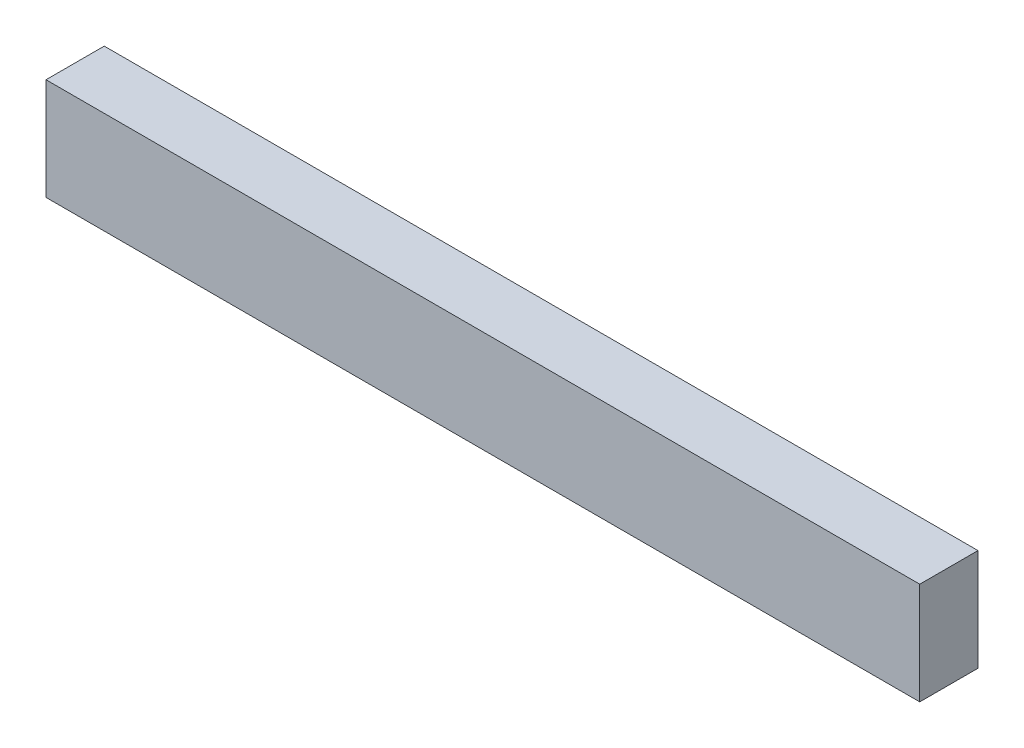
SolidWorks part; units mm, degrees
ref_plane "Front Plane" through (0, 0, 0) normal (0, 0, 1) x (1, 0, 0)
ref_plane "Top Plane" through (0, 0, 0) normal (0, 1, 0) x (1, 0, 0)
ref_plane "Right Plane" through (0, 0, 0) normal (1, 0, 0) x (0, 0, -1)
sketch "Sketch1" plane through (0, 0, 0) normal (0, 0, 1) x (1, 0, 0)
  line L1 (-14.4874, 16.216) -> (137.9126, 16.216)
  line L2 (-14.4874, 16.216) -> (-14.4874, -1.564)
  line L3 (-14.4874, -1.564) -> (137.9126, -1.564)
  line L4 (137.9126, 16.216) -> (137.9126, -1.564)
  dimension "D1" = 17.78
  dimension "D2" = 152.4
extrude "Boss-Extrude1" add sketch "Sketch1" along normal blind 10.16
